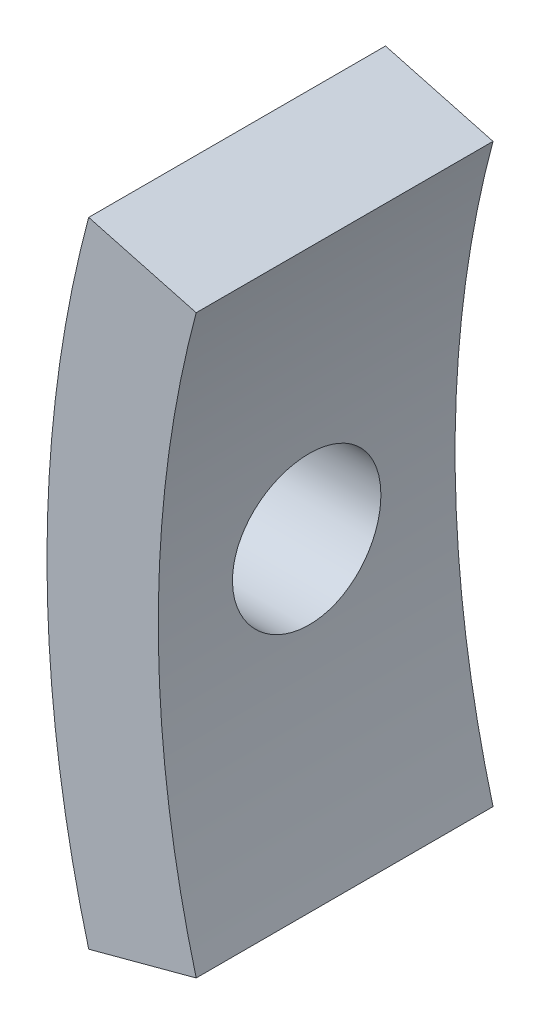
SolidWorks part; units mm, degrees
ref_plane "Front Plane" through (0, 0, 0) normal (1, 0, 0) x (0, 1, 0)
ref_plane "Top Plane" through (0, 0, 0) normal (0, 0, 1) x (0, 1, 0)
ref_plane "Right Plane" through (0, 0, 0) normal (0, 1, 0) x (-1, 0, 0)
sketch "Sketch1" plane through (0, 0, 0) normal (0, 0, 1) x (0, 1, 0)
  line L0 (0, 0) -> (-10.6763, 39.8444)
  line L1 (-10.6763, 39.8444) -> (10.6763, 39.8444)
  line L2 (10.6763, 39.8444) -> (0, 0)
  circle A0 centre (0, 0) radius 37.5
  circle A1 centre (0, 0) radius 41.25
  dimension "D1" = 75
  dimension "D2" = 82.5
  dimension "D3" = 30
extrude "Boss-Extrude1" add sketch "Sketch1" along normal blind 10 contours L1 A1 | A0 L2 L1 L0
sketch "Sketch2" plane through (0, 0, 0) normal (1, 0, 0) x (0, 1, 0)
  line L0 (0, 0) -> (0, 5) construction
  line L1 (-9.7057, 0) -> (9.7057, 0) construction
  line L2 (0, 5) -> (0, 10) construction
  line L3 (9.7057, 10) -> (-9.7057, 10) construction
  circle A0 centre (0, 5) radius 2.5
  dimension "D1" = 5
extrude "Cut-Extrude1" cut sketch "Sketch2" along normal through all both and the other way through all
